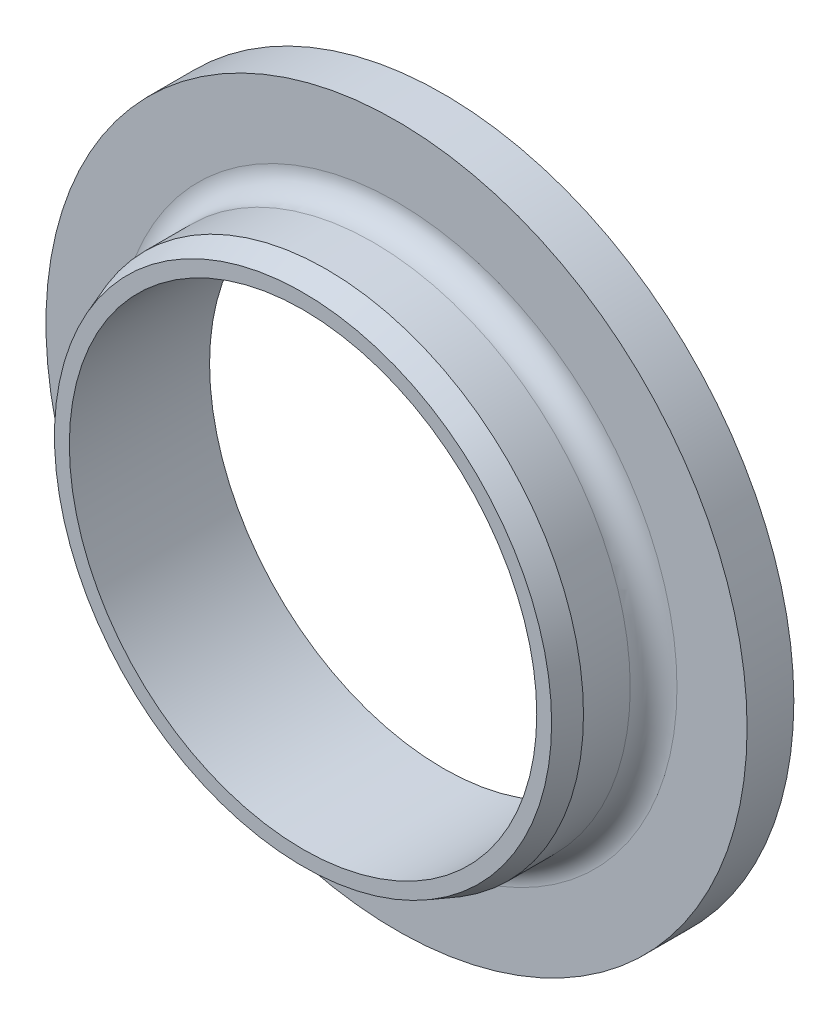
SolidWorks part; units mm, degrees
ref_plane "Ön Düzlem" through (0, 0, 0) normal (0, 0, 1) x (1, 0, 0)
ref_plane "Üst Düzlem" through (0, 0, 0) normal (0, 1, 0) x (1, 0, 0)
ref_plane "Sağ Düzlem" through (0, 0, 0) normal (1, 0, 0) x (0, 0, -1)
sketch "Sketch1" plane through (0, 0, 0) normal (0, 1, 0) x (1, 0, 0)
  line L0 (5.5, -2.5) -> (5.5, -1.5)
  line L1 (6, -1) -> (7.5, -1)
  line L2 (7.5, -1) -> (7.5, 0)
  line L3 (7.5, 0) -> (5, 0)
  line L4 (5, 0) -> (5, -3)
  line L5 (5, -3) -> (5.318, -3)
  line L6 (5.318, -3) -> (5.5, -2.5)
  line L7 (0, 0) -> (0, -3) construction
  arc A0 (5.5, -1.5) -> (6, -1) centre (6, -1.5) cw
revolve "Revolve1" add sketch "Sketch1" angle 360 about L7
